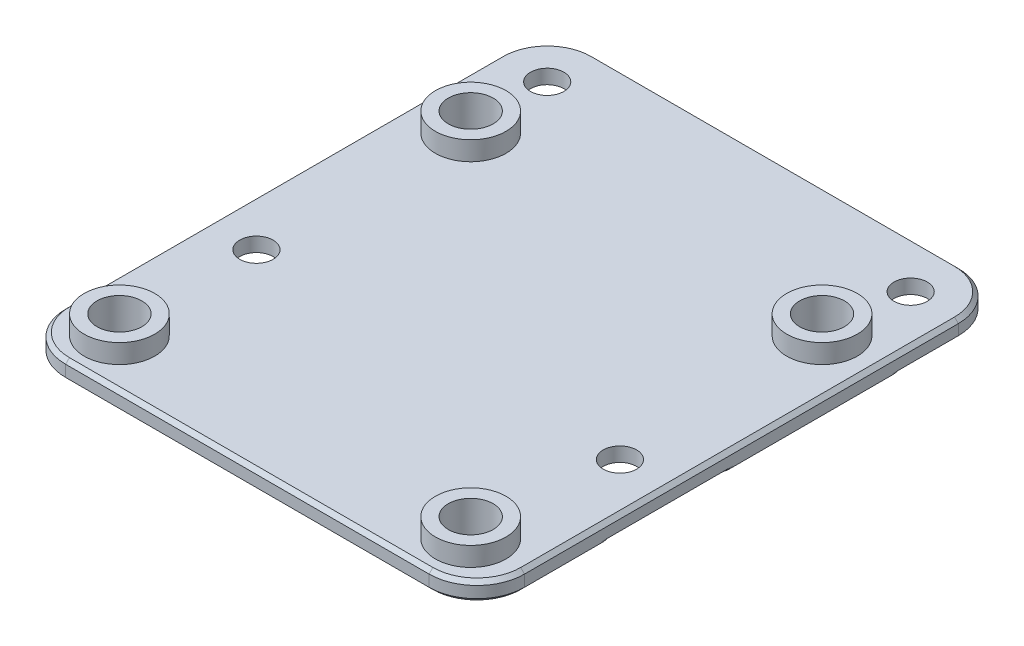
SolidWorks part; units mm, degrees
ref_plane "Front Plane" through (0, 0, 0) normal (0, 0, 1) x (1, 0, 0)
ref_plane "Top Plane" through (0, 0, 0) normal (0, 1, 0) x (1, 0, 0)
ref_plane "Right Plane" through (0, 0, 0) normal (1, 0, 0) x (0, 0, -1)
sketch "Sketch1" plane through (0, 0, 0) normal (0, 1, 0) x (1, 0, 0)
  line L0 (0, 0) -> (0, 22.74) construction
  line L1 (-24.05, -27.74) -> (24.05, -27.74)
  line L2 (-24.05, -27.74) -> (-24.05, 27.74)
  line L3 (-24.05, 27.74) -> (24.05, 27.74)
  line L4 (24.05, -27.74) -> (24.05, 27.74)
  line L5 (-24.05, -27.74) -> (24.05, 27.74) construction
  line L6 (-24.05, 27.74) -> (24.05, -27.74) construction
  line L7 (-19.05, 22.74) -> (19.05, 22.74) construction
  line L8 (-19.05, 22.74) -> (-19.05, -7.74) construction
  line L9 (-19.05, -7.74) -> (19.05, -7.74) construction
  line L10 (19.05, 22.74) -> (19.05, -7.74) construction
  line L11 (0, 0) -> (0, -22.74) construction
  line L12 (-18.4125, 14.085) -> (18.4125, 14.085) construction
  line L13 (-18.4125, 14.085) -> (-18.4125, -22.74) construction
  line L14 (-18.4125, -22.74) -> (18.4125, -22.74) construction
  line L15 (18.4125, 14.085) -> (18.4125, -22.74) construction
  circle A0 centre (19.05, 22.74) radius 1.75
  circle A1 centre (-19.05, 22.74) radius 1.75
  circle A2 centre (-19.05, -7.74) radius 1.75
  circle A3 centre (19.05, -7.74) radius 1.75
  circle A4 centre (18.4125, -22.74) radius 2.35
  circle A5 centre (-18.4125, -22.74) radius 2.35
  circle A6 centre (-18.4125, 14.085) radius 2.35
  circle A7 centre (18.4125, 14.085) radius 2.35
  point P0 (0, 0)
  point P24 (-18.4125, 12.8085)
  point P25 (-18.4125, 17.4402)
  dimension "D1" = 3.5
  dimension "D6" = 36.825
  dimension "D8" = 4.7
  dimension "D2" = 38.1
  dimension "D3" = 30.48
  dimension "D4" = 5
  dimension "D5" = 5
  dimension "D7" = 36.825
  dimension "D9" = 15
  dimension "D10" = 5
extrude "Boss-Extrude1" add sketch "Sketch1" along normal blind 1.5
fillet "Fillet1" radius 5 4 edges at (24.05, 0.75, -27.74) (24.05, 0.75, 27.74) (-24.05, 0.75, 27.74) (-24.05, 0.75, -27.74)
sketch "Sketch4" plane through (0, 1.5, 0) normal (0, 1, 0) x (1, 0, 0)
  circle A0 centre (-18.4125, -22.74) radius 3.7
  circle A1 centre (18.4125, -22.74) radius 3.7
  circle A2 centre (18.4125, 14.085) radius 3.7
  circle A3 centre (-18.4125, 14.085) radius 3.7
  circle A4 centre (18.4125, 14.085) radius 2.35 construction
  circle A5 centre (-18.4125, 14.085) radius 2.35 construction
  circle A6 centre (-18.4125, -22.74) radius 2.35 construction
  circle A7 centre (18.4125, -22.74) radius 2.35 construction
  circle A8 centre (18.4125, 14.085) radius 2.35
  circle A9 centre (-18.4125, 14.085) radius 2.35
  circle A10 centre (-18.4125, -22.74) radius 2.35
  circle A11 centre (18.4125, -22.74) radius 2.35
  dimension "D1" = 7.4
extrude "Boss-Extrude3" add sketch "Sketch4" along normal blind 2
sketch "Sketch5" plane through (0, 0, 0) normal (0, -1, 0) x (1, 0, 0)
  line L4 (-19.05, -27.74) -> (19.05, -27.74)
  line L5 (24.05, -22.74) -> (24.05, 22.74)
  line L6 (19.05, 27.74) -> (-19.05, 27.74)
  line L7 (-24.05, 22.74) -> (-24.05, -22.74)
  line L8 (-19.05, -27.74) -> (19.05, -27.74)
  line L9 (24.05, -22.74) -> (24.05, 22.74)
  line L10 (19.05, 27.74) -> (-19.05, 27.74)
  line L11 (-24.05, 22.74) -> (-24.05, -22.74)
  circle A0 centre (18.4125, 22.74) radius 2.35 construction
  circle A1 centre (18.4125, -14.085) radius 2.35 construction
  circle A2 centre (-18.4125, -14.085) radius 2.35 construction
  circle A3 centre (-18.4125, 22.74) radius 2.35 construction
  arc A4 (19.05, -27.74) -> (24.05, -22.74) centre (19.05, -22.74) ccw
  arc A5 (24.05, 22.74) -> (19.05, 27.74) centre (19.05, 22.74) ccw
  arc A6 (-19.05, 27.74) -> (-24.05, 22.74) centre (-19.05, 22.74) ccw
  arc A7 (-24.05, -22.74) -> (-19.05, -27.74) centre (-19.05, -22.74) ccw
  arc A8 (19.05, -27.74) -> (24.05, -22.74) centre (19.05, -22.74) ccw
  arc A9 (24.05, 22.74) -> (19.05, 27.74) centre (19.05, 22.74) ccw
  arc A10 (-19.05, 27.74) -> (-24.05, 22.74) centre (-19.05, 22.74) ccw
  arc A11 (-24.05, -22.74) -> (-19.05, -27.74) centre (-19.05, -22.74) ccw
  circle A12 centre (18.4125, 22.74) radius 2.35
  circle A13 centre (18.4125, -14.085) radius 2.35
  circle A14 centre (-18.4125, -14.085) radius 2.35
  circle A15 centre (-18.4125, 22.74) radius 2.35
  circle A16 centre (-19.05, 7.74) radius 5.5
  circle A17 centre (19.05, 7.74) radius 5.5
  circle A18 centre (19.05, -22.74) radius 5.5
  circle A19 centre (-19.05, -22.74) radius 5.5
  circle M12 centre (-18.4125, -14.085) radius 2.35
  circle M13 centre (18.4125, 22.74) radius 2.35
  line M18 (24.05, -22.74) -> (24.05, 22.74)
  arc M19 (24.05, 22.74) -> (19.05, 27.74) centre (19.05, 22.74) ccw
  line M20 (19.05, 27.74) -> (-19.05, 27.74)
  arc M21 (-19.05, 27.74) -> (-24.05, 22.74) centre (-19.05, 22.74) ccw
  line M22 (-24.05, 22.74) -> (-24.05, -22.74)
  circle M26 centre (-18.4125, 22.74) radius 2.35
  circle M27 centre (18.4125, -14.085) radius 2.35
  dimension "D2" = 11
  dimension "D1" = 0
extrude "Boss-Extrude4" add sketch "Sketch5" along normal blind 0.5 contours A19 L8 A18 L9 A17 A16 M18 M19 M20 M21 M22 M13 M26 M27 M12
fillet "Fillet2" radius 2 8 edges at (24.05, -0.25, 10.0313) (24.05, -0.25, 5.4487) (16.7587, -0.25, -27.74) (24.05, -0.25, -20.4487) (-24.05, -0.25, -20.4487) (-16.7587, -0.25, -27.74) (-24.05, -0.25, 5.4487) (-24.05, -0.25, 10.0313)
chamfer "Chamfer2" distance 0.4 angle 45 32 edges at (24.05, 1.5, 0) (22.5855, 1.5, -26.2755) (22.5855, 1.5, 26.2755) (0, 1.5, -27.74) (0, 1.5, 27.74) (-22.5855, 1.5, -26.2755) (-22.5855, 1.5, 26.2755) (-24.05, 1.5, 0) (-24.05, -0.5, 18.6769) (-24.05, 0, 7.74) (-24.05, -0.5, -7.5) (-15.6131, 0, -27.74) (-22.5855, 0, -26.2755) (-24.05, 0, -19.3031) (24.05, -0.5, -7.5) (23.1454, -0.5, -17.5395) (23.1454, -0.5, 2.5395) (15.1609, -0.5, -18.8509) (13.55, -0.5, 7.74) (13.8495, -0.5, -26.8354) (23.1454, -0.5, 12.9405) (0, -0.5, -27.74) (24.05, -0.5, 18.6769) (-13.8495, -0.5, -26.8354) (22.5855, -0.5, 26.2755) (-15.1609, -0.5, -18.8509) (0, -0.5, 27.74) (-23.1454, -0.5, -17.5395) (-22.5855, -0.5, 26.2755) (-23.1454, -0.5, 2.5395) (-23.1454, -0.5, 12.9405) (-13.55, -0.5, 7.74)
